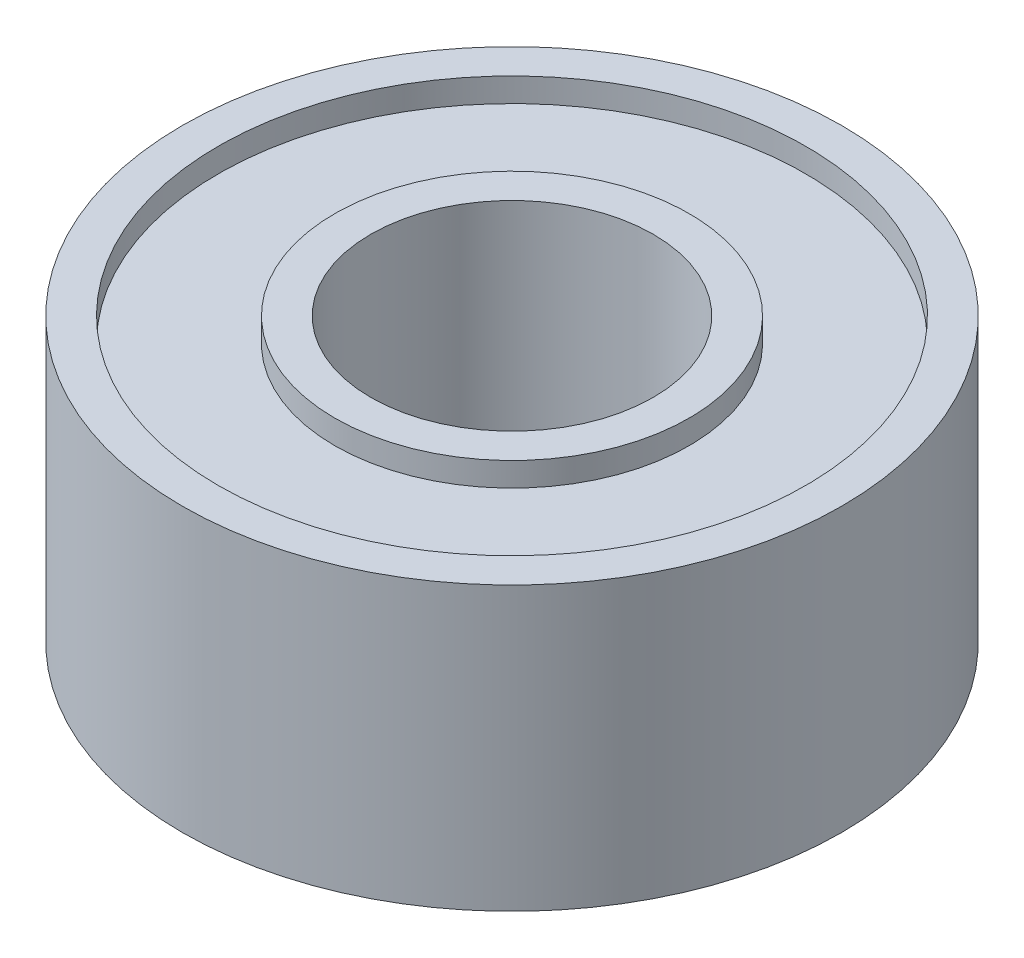
SolidWorks part; units mm, degrees
material "Alloy Steel (SS)"
ref_plane "Front Plane" through (0, 0, 0) normal (0, 0, 1) x (1, 0, 0)
ref_plane "Top Plane" through (0, 0, 0) normal (0, 1, 0) x (1, 0, 0)
ref_plane "Right Plane" through (0, 0, 0) normal (1, 0, 0) x (0, 0, -1)
sketch "Sketch1" plane through (0, 0, 0) normal (0, 1, 0) x (1, 0, 0)
  circle A0 centre (0, 0) radius 1.5
  circle A1 centre (0, 0) radius 3.5
  dimension "D1" = 3
  dimension "D2" = 7
extrude "Boss-Extrude1" add sketch "Sketch1" along normal mid plane 3
sketch "Sketch2" plane through (0, 1.5, 0) normal (0, 1, 0) x (1, 0, 0)
  circle A0 centre (0, 0) radius 1.881
  circle A1 centre (0, 0) radius 3.119
  circle A2 centre (0, 0) radius 1.5 construction
  circle A3 centre (0, 0) radius 3.5 construction
  dimension "D1" = 0.381
  dimension "D2" = 0.381
extrude "Cut-Extrude1" cut sketch "Sketch2" against normal blind 0.254
mirror "Mirror1" about plane through (0, 0, 0) normal (0, 1, 0) of "Cut-Extrude1"
